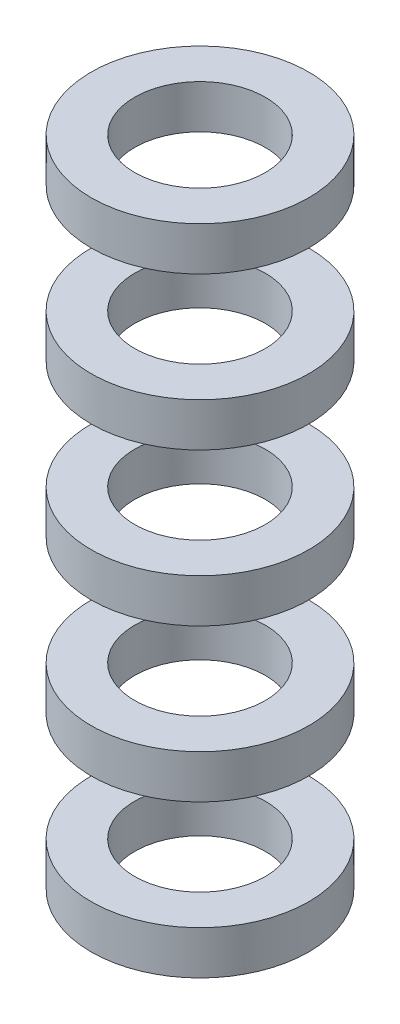
SolidWorks part; units mm, degrees
ref_plane "前视基准面" through (0, 0, 0) normal (0, 0, 1) x (1, 0, 0)
ref_plane "上视基准面" through (0, 0, 0) normal (0, 1, 0) x (1, 0, 0)
ref_plane "右视基准面" through (0, 0, 0) normal (1, 0, 0) x (0, 0, -1)
sketch "草图1" plane through (0, 0, 0) normal (0, 1, 0) x (1, 0, 0)
  circle A0 centre (0, 0) radius 30
  circle A1 centre (0, 0) radius 50
  dimension "D1" = 100
  dimension "D2" = 60
extrude "凸台-拉伸1" add sketch "草图1" along normal blind 300
ref_plane "基准面1" through (0, 0, 50) normal (0, 0, 1) x (1, 0, 0)
sketch "草图2" plane through (0, 0, 50) normal (0, 0, 1) x (1, 0, 0)
  line L1 (-50, 300) -> (-50, 0) construction
  line L2 (-50, 280) -> (-50, 230)
  line L4 (-50, 210) -> (-50, 160)
  line L6 (-50, 140) -> (-50, 90)
  line L8 (-50, 70) -> (-50, 20)
  line L12 (50, 20) -> (-50, 20)
  line L13 (50, 20) -> (50, 70)
  line L14 (50, 70) -> (-50, 70)
  line L16 (-50, 90) -> (50, 90)
  line L17 (50, 90) -> (50, 140)
  line L18 (50, 140) -> (-50, 140)
  line L19 (-50, 160) -> (50, 160)
  line L21 (-50, 210) -> (50, 210)
  line L22 (50, 210) -> (50, 160)
  line L23 (-50, 230) -> (50, 230)
  line L25 (-50, 280) -> (50, 280)
  line L26 (50, 280) -> (50, 230)
  point P25 (0, 0)
  dimension "D2" = 50
extrude "切除-拉伸1" cut sketch "草图2" against normal blind 300
